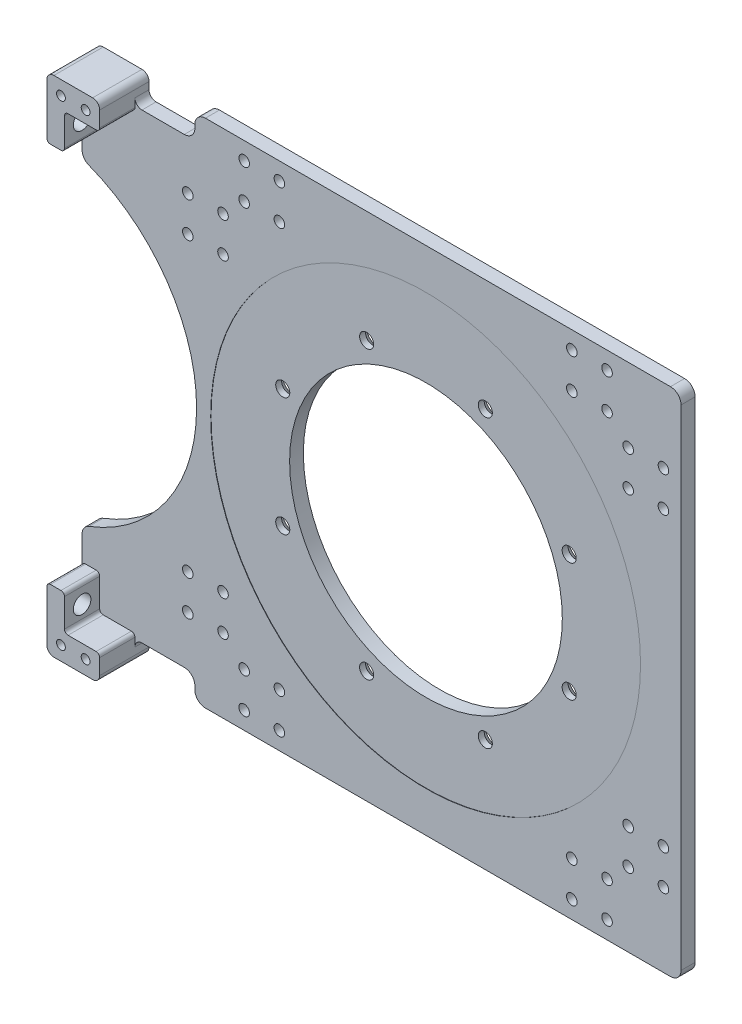
SolidWorks part; units mm, degrees
material "6061 合金"
ref_plane "前视基准面" through (0, 0, 0) normal (0, 0, 1) x (1, 0, 0)
ref_plane "上视基准面" through (0, 0, 0) normal (0, 1, 0) x (1, 0, 0)
ref_plane "右视基准面" through (0, 0, 0) normal (1, 0, 0) x (0, 0, -1)
other "Configuration Table"
sketch "草图1" plane through (0, 0, 0) normal (0, 0, 1) x (1, 0, 0)
  line L0 (0, 0) -> (16.8381, 40.6507) construction
  line L1 (-72.5, 72.5) -> (72.5, 72.5)
  line L2 (-72.5, 72.5) -> (-72.5, -72.5)
  line L3 (-72.5, -72.5) -> (72.5, -72.5)
  line L4 (72.5, 72.5) -> (72.5, -72.5)
  line L5 (-72.5, 72.5) -> (72.5, -72.5) construction
  line L6 (-72.5, -72.5) -> (72.5, 72.5) construction
  circle A0 centre (0, 0) radius 44 construction
  circle A1 centre (0, 0) radius 38.7
  circle A2 centre (16.8381, 40.6507) radius 2
  circle A3 centre (40.6507, 16.8381) radius 2
  circle A4 centre (40.6507, -16.8381) radius 2
  circle A5 centre (16.8381, -40.6507) radius 2
  circle A6 centre (-16.8381, -40.6507) radius 2
  circle A7 centre (-40.6507, -16.8381) radius 2
  circle A8 centre (-40.6507, 16.8381) radius 2
  circle A9 centre (-16.8381, 40.6507) radius 2
  circle A10 centre (41.5, -67.5) radius 1.5 construction
  circle A11 centre (51.5, -67.5) radius 1.5 construction
  circle A12 centre (41.5, -57.5) radius 1.5 construction
  circle A13 centre (51.5, -57.5) radius 1.5 construction
  circle A14 centre (57.5, -51.5) radius 1.5 construction
  circle A15 centre (57.5, -41.5) radius 1.5 construction
  circle A16 centre (67.5, -41.5) radius 1.5 construction
  circle A17 centre (67.5, -51.5) radius 1.5 construction
  circle A18 centre (-51.5, -67.5) radius 1.5 construction
  circle A19 centre (-41.5, -67.5) radius 1.5 construction
  circle A20 centre (-41.5, -57.5) radius 1.5 construction
  circle A21 centre (-51.5, -57.5) radius 1.5 construction
  circle A22 centre (-57.5, -51.5) radius 1.5 construction
  circle A23 centre (-57.5, -41.5) radius 1.5 construction
  circle A24 centre (-67.5, -41.5) radius 1.5 construction
  circle A25 centre (-67.5, -51.5) radius 1.5 construction
  circle A26 centre (-41.5, 67.5) radius 1.5 construction
  circle A27 centre (-41.5, 57.5) radius 1.5 construction
  circle A28 centre (-51.5, 57.5) radius 1.5 construction
  circle A29 centre (-51.5, 67.5) radius 1.5 construction
  circle A30 centre (51.5, 57.5) radius 1.5 construction
  circle A31 centre (51.5, 67.5) radius 1.5 construction
  circle A32 centre (41.5, 67.5) radius 1.5 construction
  circle A33 centre (41.5, 57.5) radius 1.5 construction
  circle A34 centre (57.5, 51.5) radius 1.5 construction
  circle A35 centre (57.5, 41.5) radius 1.5 construction
  circle A36 centre (67.5, 41.5) radius 1.5 construction
  circle A37 centre (67.5, 51.5) radius 1.5 construction
  circle A38 centre (41.5, -67.5) radius 1.5
  circle A39 centre (51.5, -67.5) radius 1.5
  circle A40 centre (41.5, -57.5) radius 1.5
  circle A41 centre (51.5, -57.5) radius 1.5
  circle A42 centre (57.5, -51.5) radius 1.5
  circle A43 centre (57.5, -41.5) radius 1.5
  circle A44 centre (67.5, -41.5) radius 1.5
  circle A45 centre (67.5, -51.5) radius 1.5
  circle A46 centre (-51.5, -67.5) radius 1.5
  circle A47 centre (-41.5, -67.5) radius 1.5
  circle A48 centre (-41.5, -57.5) radius 1.5
  circle A49 centre (-51.5, -57.5) radius 1.5
  circle A50 centre (-57.5, -51.5) radius 1.5
  circle A51 centre (-57.5, -41.5) radius 1.5
  circle A52 centre (-67.5, -41.5) radius 1.5
  circle A53 centre (-67.5, -51.5) radius 1.5
  circle A54 centre (-41.5, 67.5) radius 1.5
  circle A55 centre (-41.5, 57.5) radius 1.5
  circle A56 centre (-51.5, 57.5) radius 1.5
  circle A57 centre (-51.5, 67.5) radius 1.5
  circle A58 centre (51.5, 57.5) radius 1.5
  circle A59 centre (51.5, 67.5) radius 1.5
  circle A60 centre (41.5, 67.5) radius 1.5
  circle A61 centre (41.5, 57.5) radius 1.5
  circle A62 centre (57.5, 51.5) radius 1.5
  circle A63 centre (57.5, 41.5) radius 1.5
  circle A64 centre (67.5, 41.5) radius 1.5
  circle A65 centre (67.5, 51.5) radius 1.5
  circle A66 centre (-67.5, 41.5) radius 1.5 construction
  circle A67 centre (-57.5, 41.5) radius 1.5 construction
  circle A68 centre (-67.5, 51.5) radius 1.5 construction
  circle A69 centre (-57.5, 51.5) radius 1.5 construction
  circle A70 centre (-67.5, 41.5) radius 1.5
  circle A71 centre (-57.5, 41.5) radius 1.5
  circle A72 centre (-67.5, 51.5) radius 1.5
  circle A73 centre (-57.5, 51.5) radius 1.5
  point P0 (0, 0)
  point P28 (0, 0)
  dimension "D3" = 88
  dimension "D4" = 77.4
  dimension "D7" = 4
  dimension "D1" = 145
  dimension "D2" = 145
  dimension "D5" = 22.5
  dimension "D6" = 8
extrude "凸台-拉伸1" add sketch "草图1" along normal blind 4
sketch "草图2" plane through (0, 0, 4) normal (0, 0, 1) x (1, 0, 0)
  circle A0 centre (0, 0) radius 61
extrude "切除-拉伸1" cut sketch "草图2" against normal blind 0.1
sketch "草图3" plane through (0, 0, 0) normal (0, 0, -1) x (-1, 0, 0)
  line L1 (97.5, -72.5) -> (72.5, -72.5)
  line L2 (97.5, -72.5) -> (97.5, 72.5)
  line L3 (97.5, 72.5) -> (72.5, 72.5)
  line L4 (72.5, -72.5) -> (72.5, 72.5)
  line L5 (97.5, -72.5) -> (72.5, 72.5) construction
  line L6 (97.5, 72.5) -> (72.5, -72.5) construction
  line L7 (90.5, 65.5) -> (97.5, 65.5)
  line L8 (90.5, 65.5) -> (90.5, 72.5)
  line L9 (90.5, 72.5) -> (97.5, 72.5)
  line L10 (97.5, 65.5) -> (97.5, 72.5)
  line L11 (90.5, 65.5) -> (97.5, 72.5) construction
  line L12 (90.5, 72.5) -> (97.5, 65.5) construction
  line L13 (90.5, -65.5) -> (97.5, -65.5)
  line L14 (90.5, -65.5) -> (90.5, -72.5)
  line L15 (90.5, -72.5) -> (97.5, -72.5)
  line L16 (97.5, -65.5) -> (97.5, -72.5)
  line L17 (90.5, -65.5) -> (97.5, -72.5) construction
  line L18 (90.5, -72.5) -> (97.5, -65.5) construction
  circle A0 centre (112.5, 0) radius 47.5
  point P2 (85, 0)
  point P9 (94, 69)
  point P10 (94, -69)
  line M8 (72.5, -72.5) -> (72.5, 72.5)
  dimension "D1" = 95
  dimension "D2" = 112.5
  dimension "D3" = 25
  dimension "D4" = 7
  dimension "D5" = 7
  dimension "D6" = 7
  dimension "D7" = 7
extrude "凸台-拉伸2" add sketch "草图3" against normal blind 4 contours A0 L2 L7 L8 L3 M8 | A0 L1 L14 L13 L2 M8 | L4 A0
chamfer "倒角1" distance 2.2 angle 45 8 edges at (-14.8381, -40.6507, 0) (18.8381, -40.6507, 0) (42.6507, -16.8381, 0) (42.6507, 16.8381, 0) (18.8381, 40.6507, 0) (-14.8381, 40.6507, 0) (-38.6507, -16.8381, 0) (-38.6507, 16.8381, 0)
sketch "草图4" plane through (0, 0, 0) normal (0, 0, -1) x (-1, 0, 0)
  line L1 (18.9091, 45.6507) -> (45.6507, 18.9091) construction
  line L2 (45.6507, 18.9091) -> (45.6507, -18.9091) construction
  line L3 (45.6507, -18.9091) -> (18.9091, -45.6507) construction
  line L4 (18.9091, -45.6507) -> (-18.9091, -45.6507) construction
  line L5 (-18.9091, -45.6507) -> (-45.6507, -18.9091) construction
  line L6 (-45.6507, -18.9091) -> (-45.6507, 18.9091) construction
  line L7 (-45.6507, 18.9091) -> (-18.9091, 45.6507) construction
  line L8 (-50.5, 34.5) -> (-67.5, 34.5) construction
  line L9 (-65.5, 28.5) -> (-65.5, -28.5)
  line L10 (-51.5, 57.5) -> (-41.5, 57.5) construction
  line L11 (-41.5, 57.5) -> (-41.5, 67.5) construction
  line L12 (-57.5, 51.5) -> (-57.5, 41.5) construction
  line L13 (-57.5, 41.5) -> (-67.5, 41.5) construction
  line L14 (-34.5, 50.5) -> (-34.5, 67.5) construction
  line L15 (-50.5, 34.5) -> (-34.5, 34.5)
  line L16 (-50.5, 50.5) -> (-34.5, 50.5)
  line L17 (-34.5, 50.5) -> (-34.5, 65.5) construction
  line L18 (-50.5, 50.5) -> (-50.5, 34.5)
  line L19 (-50.5, 34.5) -> (-65.5, 34.5) construction
  line L21 (-28.5, 65.5) -> (-28.5, 43.4943)
  line L23 (-28.5, 65.5) -> (28.5, 65.5)
  line L24 (28.5, 65.5) -> (28.5, 43.4943)
  line L25 (-72.5, 72.5) -> (90.5, 72.5) construction
  line L26 (0, 0) -> (-72.5, 0) construction
  line L27 (-72.5, -72.5) -> (-72.5, 72.5) construction
  line L28 (-65.5, 28.5) -> (-43.4943, 28.5)
  line L40 (-34.5, 34.5) -> (-34.5, 50.5)
  line L41 (-34.5, -34.5) -> (-34.5, -50.5)
  line L42 (-16.8381, 40.6507) -> (16.8381, 40.6507) construction
  line L43 (16.8381, 40.6507) -> (40.6507, 16.8381) construction
  line L44 (40.6507, 16.8381) -> (40.6507, -16.8381) construction
  line L45 (40.6507, -16.8381) -> (16.8381, -40.6507) construction
  line L46 (16.8381, -40.6507) -> (-16.8381, -40.6507) construction
  line L47 (-16.8381, -40.6507) -> (-40.6507, -16.8381) construction
  line L48 (-40.6507, -16.8381) -> (-40.6507, 16.8381) construction
  line L49 (-40.6507, 16.8381) -> (-16.8381, 40.6507) construction
  line L50 (-50.5, -50.5) -> (-34.5, -50.5)
  line L51 (0, 0) -> (0, 83.6324) construction
  line L52 (-50.5, -50.5) -> (-50.5, -34.5)
  line L53 (-18.9091, 45.6507) -> (18.9091, 45.6507) construction
  line L54 (-50.5, -34.5) -> (-34.5, -34.5)
  line L55 (-65.5, -28.5) -> (-43.4943, -28.5)
  line L56 (-50.5, 51.5) -> (-50.5, 34.5) construction
  line L57 (-51.5, 50.5) -> (-34.5, 50.5) construction
  line L58 (50.5, -34.5) -> (34.5, -34.5)
  line L59 (34.5, -34.5) -> (34.5, -50.5)
  line L60 (50.5, -50.5) -> (34.5, -50.5)
  line L61 (50.5, -50.5) -> (50.5, -34.5)
  line L62 (65.5, -28.5) -> (43.4943, -28.5)
  line L63 (65.5, 28.5) -> (65.5, -28.5)
  line L64 (65.5, 28.5) -> (43.4943, 28.5)
  line L65 (50.5, 50.5) -> (50.5, 34.5)
  line L66 (50.5, 50.5) -> (34.5, 50.5)
  line L67 (34.5, 34.5) -> (34.5, 50.5)
  line L68 (50.5, 34.5) -> (34.5, 34.5)
  line L69 (28.5, -65.5) -> (28.5, -43.4943)
  line L70 (-28.5, -65.5) -> (28.5, -65.5)
  line L71 (-28.5, -65.5) -> (-28.5, -43.4943)
  circle A0 centre (0, 0) radius 52
  point P24 (0, 65.5)
  dimension "D5" = 104
  dimension "D1" = 6
  dimension "D6" = 7
  dimension "D7" = 6
  dimension "D2" = 7
  dimension "D3" = 7
  dimension "D4" = 5
extrude "切除-拉伸2" cut sketch "草图4" against normal blind 3
fillet "圆角3" radius 3 36 edges at (-28.5, 43.4943, 1.5) (-28.5, 65.5, 1.5) (28.5, 43.4943, 1.5) (-43.4943, -28.5, 1.5) (-65.5, -28.5, 1.5) (-65.5, 28.5, 1.5) (-43.4943, 28.5, 1.5) (38.9069, -34.5, 1.5) (50.5, -34.5, 1.5) (50.5, -50.5, 1.5) (34.5, -50.5, 1.5) (34.5, -38.9069, 1.5) (43.4943, 28.5, 1.5) (65.5, 28.5, 1.5) (65.5, -28.5, 1.5) (43.4943, -28.5, 1.5) (34.5, 38.9069, 1.5) (34.5, 50.5, 1.5) (50.5, 34.5, 1.5) (38.9069, 34.5, 1.5) (28.5, -43.4943, 1.5) (28.5, -65.5, 1.5) (-28.5, -65.5, 1.5) (-28.5, -43.4943, 1.5) (-34.5, -38.9069, 1.5) (-34.5, -50.5, 1.5) (-50.5, -50.5, 1.5) (-50.5, -34.5, 1.5) (-38.9069, -34.5, 1.5) (-38.9069, 34.5, 1.5) (-50.5, 34.5, 1.5) (-50.5, 50.5, 1.5) (-34.5, 50.5, 1.5) (-34.5, 38.9069, 1.5) (50.5, 50.5, 1.5) (28.5, 65.5, 1.5)
sketch "草图5" plane through (0, 0, 0) normal (0, 0, -1) x (-1, 0, 0)
  line L0 (65.5, 72.5) -> (90.5, 72.5)
  line L1 (65.5, 72.5) -> (65.5, 65.5)
  line L2 (90.5, 72.5) -> (90.5, 65.5)
  line L3 (65.5, 65.5) -> (90.5, 65.5)
  line L4 (-72.5, 72.5) -> (90.5, 72.5) construction
  line L7 (65.5, -72.5) -> (90.5, -72.5)
  line L8 (65.5, -72.5) -> (65.5, -65.5)
  line L9 (90.5, -72.5) -> (90.5, -65.5)
  line L10 (65.5, -65.5) -> (90.5, -65.5)
  line L11 (90.5, -72.5) -> (-72.5, -72.5) construction
  line L13 (90.5, 65.5) -> (97.5, 65.5) construction
  line L14 (90.5, -65.5) -> (97.5, -65.5) construction
  circle A0 centre (112.5, 0) radius 47.5
  dimension "D1" = 25
  dimension "D2" = 25
extrude "切除-拉伸3" cut sketch "草图5" against normal blind 4
fillet "圆角4" radius 3 10 edges at (-97.5, -45.0694, 2) (-97.5, 45.0694, 2) (-65.5, 6.8739, 1.5) (-65.5, -6.8739, 1.5) (72.5, -72.5, 2) (72.5, 72.5, 2) (-65.5, 72.5, 2) (-65.5, 65.5, 2) (-65.5, -65.5, 2) (-65.5, -72.5, 2)
sketch "草图7" plane through (0, 0, 0) normal (0, 0, -1) x (-1, 0, 0)
  line L0 (82.5, -65.5) -> (97.5, -65.5)
  line L1 (82.5, -65.5) -> (82.5, -71.5)
  line L2 (97.5, -65.5) -> (97.5, -71.5)
  line L3 (82.5, -71.5) -> (97.5, -71.5)
  line L4 (68.5, -65.5) -> (97.5, -65.5) construction
  dimension "D1" = 6
  dimension "D2" = 15
extrude "凸台-拉伸3" add sketch "草图7" against normal blind 4
sketch "草图8" plane through (0, 0, 4) normal (0, 0, 1) x (1, 0, 0)
  line L0 (-82.5, -71.5) -> (-97.5, -71.5)
  line L4 (-97.5, -54.1) -> (-92.5, -54.1)
  line L8 (-97.5, -71.5) -> (-97.5, -47.1832) construction
  line L9 (-68.5, -65.5) -> (-82.5, -65.5) construction
  line L10 (-97.5, -54.1) -> (-97.5, -71.5)
  line L11 (-92.5, -54.1) -> (-92.5, -64.1)
  line L12 (-92.5, -64.1) -> (-82.5, -64.1)
  line L13 (-82.5, -64.1) -> (-82.5, -65.5)
  line L14 (-82.5, -65.5) -> (-82.5, -71.5)
  circle A0 centre (-93.5, -67.5) radius 1.25
  circle A1 centre (-86.5, -67.5) radius 1.25
  dimension "D4" = 2.5
  dimension "D6" = 4
  dimension "D7" = 4
  dimension "D8" = 4
  dimension "D1" = 5
  dimension "D2" = 11.4
  dimension "D3" = 10
  dimension "D5" = 4
extrude "凸台-拉伸4" add sketch "草图8" along normal blind 10
sketch "草图9" plane through (-92.5, 0, 0) normal (1, 0, 0) x (0, 0, -1)
  line L0 (-14, -54.1) -> (-4, -54.1) construction
  line L1 (-14, -64.1) -> (-14, -54.1) construction
  circle A0 centre (-9, -59.5) radius 2.5
  point P2 (0, 0)
  dimension "D1" = 5
  dimension "D2" = 5.4
  dimension "D3" = 5
extrude "切除-拉伸4" cut sketch "草图9" against normal blind 10
sketch "草图10" plane through (0, 0, 4) normal (0, 0, 1) x (1, 0, 0)
  circle A0 centre (-93.5, -67.5) radius 1.25
  circle A1 centre (-86.5, -67.5) radius 1.25
extrude "切除-拉伸5" cut sketch "草图10" against normal blind 10
mirror "镜向1" about plane through (0, 0, 0) normal (0, 1, 0) of "切除-拉伸5", "切除-拉伸4", "凸台-拉伸4", "凸台-拉伸3"
fillet "圆角5" radius 2 6 edges at (-97.5, 71.5, 7) (-82.5, 71.5, 7) (-82.5, 65.5, 2) (-82.5, -71.5, 7) (-82.5, -65.5, 2) (-97.5, -71.5, 7)
fillet "圆角6" radius 1 8 edges at (-82.5, 64.1, 9) (-82.5, -64.1, 9) (-92.5, -64.1, 9) (-92.5, -54.1, 9) (-97.5, -54.1, 9) (-92.5, 64.1, 9) (-92.5, 54.1, 9) (-97.5, 54.1, 9)
